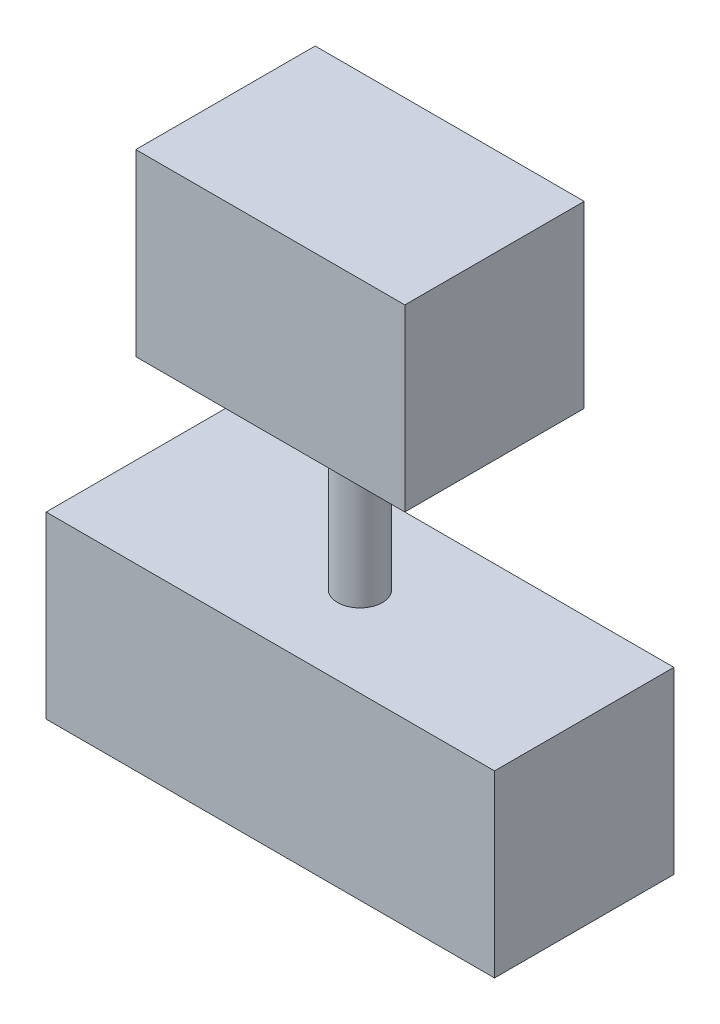
SolidWorks part; units mm, degrees
ref_plane "Front Plane" through (0, 0, 0) normal (0, 0, 1) x (1, 0, 0)
ref_plane "Top Plane" through (0, 0, 0) normal (0, 1, 0) x (1, 0, 0)
ref_plane "Right Plane" through (0, 0, 0) normal (1, 0, 0) x (0, 0, -1)
sketch "Sketch1" plane through (0, 0, 0) normal (0, 0, 1) x (1, 0, 0)
  line L1 (-25, -10) -> (25, -10)
  line L2 (-25, -10) -> (-25, 10)
  line L3 (-25, 10) -> (25, 10)
  line L4 (25, -10) -> (25, 10)
  line L5 (-25, -10) -> (25, 10) construction
  line L6 (-25, 10) -> (25, -10) construction
  point P0 (0, 0)
  dimension "D1" = 50
  dimension "D2" = 20
extrude "Boss-Extrude1" add sketch "Sketch1" along normal blind 20
sketch "Sketch2" plane through (0, 10, 0) normal (0, 1, 0) x (1, 0, 0)
  line L0 (-25, -10) -> (0, -10) construction
  line L1 (-25, -20) -> (-25, 0) construction
  circle A0 centre (0, -10) radius 2.5
  dimension "D1" = 5
extrude "Boss-Extrude2" add sketch "Sketch2" along normal blind 20 separate body
sketch "Sketch3" plane through (0, 0, 0) normal (0, 0, 1) x (1, 0, 0)
  line L0 (2.5, 30) -> (-2.5, 30) construction
  line L1 (15, 50) -> (-15, 50)
  line L2 (15, 50) -> (15, 30)
  line L3 (15, 30) -> (-15, 30)
  line L4 (-15, 50) -> (-15, 30)
  line L5 (25, -10) -> (25, 10) construction
  point P8 (0, 30)
  dimension "D1" = 30
extrude "Boss-Extrude3" add sketch "Sketch3" along normal blind 20 separate body
